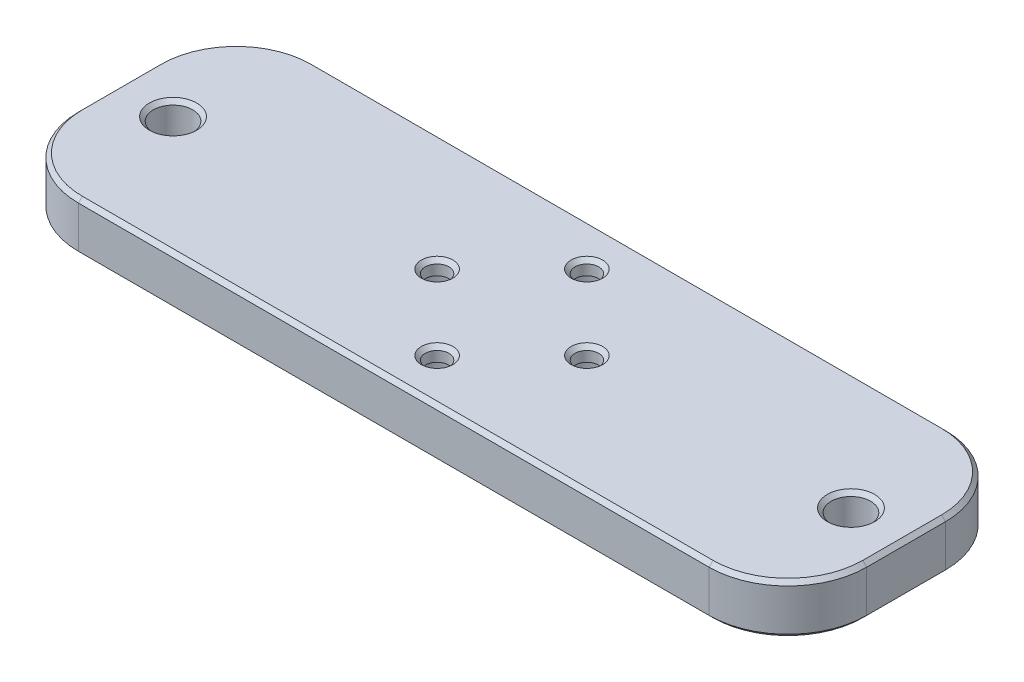
SolidWorks part; units mm, degrees
material "1060 Alloy"
ref_plane "Front Plane" through (0, 0, 0) normal (0, 0, 1) x (1, 0, 0)
ref_plane "Top Plane" through (0, 0, 0) normal (0, 1, 0) x (1, 0, 0)
ref_plane "Right Plane" through (0, 0, 0) normal (1, 0, 0) x (0, 0, -1)
sketch "Sketch1" plane through (0, 0, 0) normal (0, 1, 0) x (1, 0, 0)
  line L0 (43, 0) -> (50, 0) construction
  line L1 (40, 15) -> (-40, 15)
  line L2 (50, 5) -> (50, -5)
  line L3 (40, -15) -> (-40, -15)
  line L4 (-50, 5) -> (-50, -5)
  line L5 (50, 15) -> (-50, -15) construction
  line L6 (50, -15) -> (-50, 15) construction
  line L7 (0, -55) -> (0, 55) construction
  line L8 (0, 0) -> (0, -9.5) construction
  line L9 (0, 0) -> (0, 9.5) construction
  line L10 (0, 0) -> (-9.5, 0) construction
  line L11 (0, 0) -> (9.5, 0) construction
  arc A0 (-40, 15) -> (-50, 5) centre (-40, 5) ccw
  arc A1 (-50, -5) -> (-40, -15) centre (-40, -5) ccw
  arc A2 (50, -5) -> (40, -15) centre (40, -5) cw
  arc A3 (50, 5) -> (40, 15) centre (40, 5) ccw
  circle A4 centre (43, 0) radius 2.5
  circle A5 centre (-43, 0) radius 2.5
  circle A6 centre (0, -9.5) radius 1.5
  circle A7 centre (-9.5, 0) radius 1.5
  circle A8 centre (0, 9.5) radius 1.5
  circle A9 centre (9.5, 0) radius 1.5
  point P0 (0, 0)
  dimension "D3" = 10
  dimension "D5" = 5
  dimension "D7" = 3
  dimension "D1" = 30
  dimension "D2" = 100
  dimension "D4" = 7
  dimension "D6" = 9.5
extrude "Boss-Extrude1" add sketch "Sketch1" along normal blind 6.3
sketch "Sketch2" plane through (0, 0, 0) normal (0, -1, 0) x (1, 0, 0)
  circle A0 centre (0, 9.5) radius 3.25
  circle A1 centre (9.5, 0) radius 3.25
  circle A2 centre (0, -9.5) radius 3.25
  circle A3 centre (-9.5, 0) radius 3.25
  dimension "D1" = 6.5
extrude "Cut-Extrude1" cut sketch "Sketch2" against normal blind 4.5
chamfer "Chamfer1" distance 0.5 angle 45 28 edges at (9.5, 6.3, 1.5) (-9.5, 6.3, 1.5) (-43, 6.3, -2.5) (0, 6.3, -15) (47.0711, 6.3, -12.0711) (50, 6.3, 0) (47.0711, 6.3, 12.0711) (0, 6.3, 15) (-47.0711, 6.3, 12.0711) (-50, 6.3, 0) (-47.0711, 6.3, -12.0711) (43, 6.3, 2.5) (0, 6.3, 11) (0, 6.3, -8) (-43, 0, -2.5) (43, 0, 2.5) (-50, 0, 0) (-47.0711, 0, 12.0711) (0, 0, 15) (47.0711, 0, 12.0711) (50, 0, 0) (47.0711, 0, -12.0711) (0, 0, -15) (-47.0711, 0, -12.0711) (-9.5, 0, -3.25) (0, 0, -12.75) (9.5, 0, -3.25) (0, 0, 6.25)
